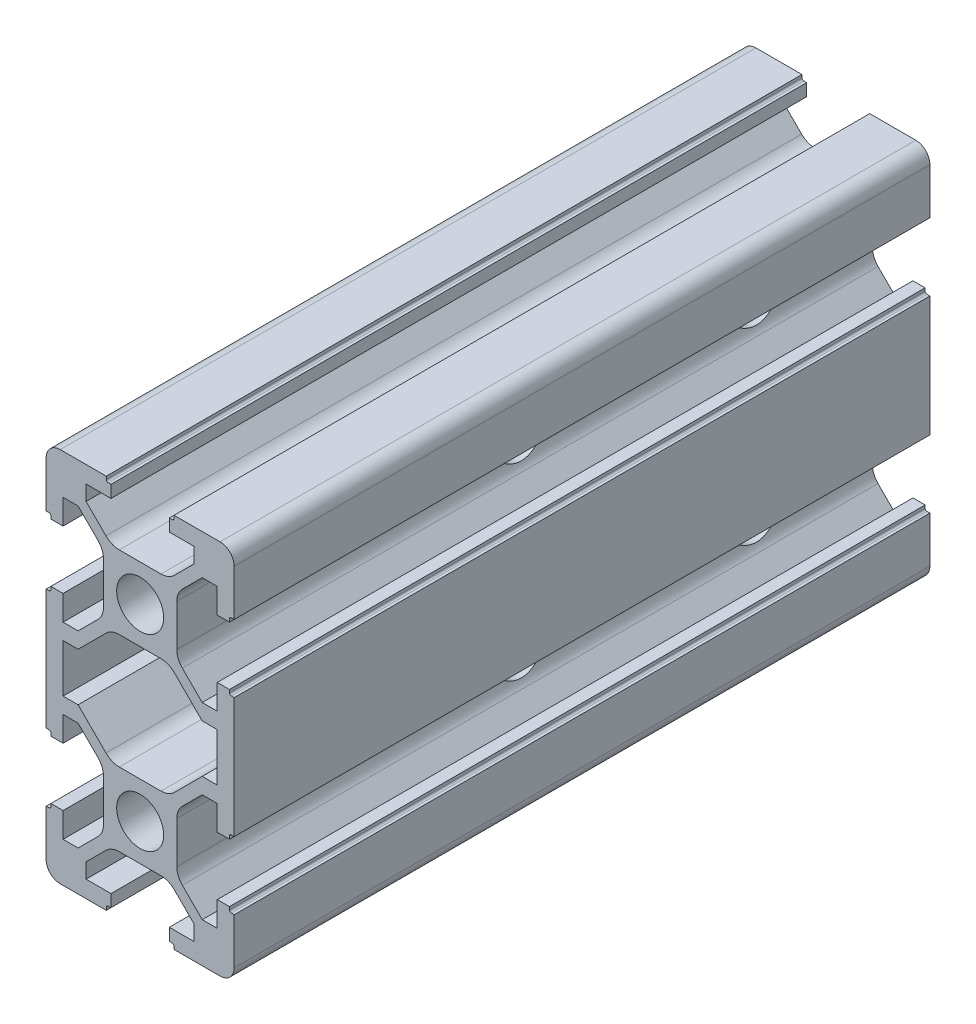
SolidWorks part; units mm, degrees
ref_plane "Alzado" through (0, 0, 0) normal (0, 0, 1) x (1, 0, 0)
ref_plane "Planta" through (0, 0, 0) normal (0, 1, 0) x (1, 0, 0)
ref_plane "Vista lateral" through (0, 0, 0) normal (1, 0, 0) x (0, 0, -1)
sketch "Croquis1" plane through (0, 0, 0) normal (0, 0, 1) x (1, 0, 0)
  line L0 (0, 0) -> (-10, -10) construction
  line L32 (0, 0) -> (-3.9, 0) construction
  line L58 (0, 0) -> (0, -3.9) construction
  line L60 (-4.4858, -3.6373) -> (-6.6, -5.7515)
  line L61 (-6.6, -5.7515) -> (-8.2, -5.7515)
  line L110 (-8.2, -5.7515) -> (-8.2, -3.1)
  line L111 (-8.2, -3.1) -> (-9.5, -3.1)
  line L112 (-9.5, -3.1) -> (-9.5, -3.4)
  line L113 (-9.7, -3.6) -> (-10, -3.6)
  line L114 (-10, -3.6) -> (-10, -8.5)
  line L115 (-3.6373, -4.4858) -> (-5.7515, -6.6)
  line L116 (-5.7515, -6.6) -> (-5.7515, -8.2)
  line L117 (-3.1, -8.2) -> (-3.1, -9.5)
  line L118 (-5.7515, -8.2) -> (-3.1, -8.2)
  line L119 (-3.1, -9.5) -> (-3.4, -9.5)
  line L120 (-3.6, -9.7) -> (-3.6, -10)
  line L121 (-3.6, -10) -> (-8.5, -10)
  line L122 (9.7, -3.6) -> (10, -3.6)
  line L123 (9.5, -3.1) -> (9.5, -3.4)
  line L124 (8.2, -3.1) -> (9.5, -3.1)
  line L125 (3.6, -10) -> (8.5, -10)
  line L126 (3.6, -9.7) -> (3.6, -10)
  line L127 (3.1, -9.5) -> (3.4, -9.5)
  line L128 (5.7515, -8.2) -> (3.1, -8.2)
  line L129 (3.1, -8.2) -> (3.1, -9.5)
  line L130 (5.7515, -6.6) -> (5.7515, -8.2)
  line L131 (3.6373, -4.4858) -> (5.7515, -6.6)
  line L132 (10, -3.6) -> (10, -8.5)
  line L133 (8.2, -5.7515) -> (8.2, -3.1)
  line L134 (6.6, -5.7515) -> (8.2, -5.7515)
  line L135 (4.4858, -3.6373) -> (6.6, -5.7515)
  line L136 (5.7515, 8.2) -> (3.1, 8.2)
  line L137 (3.6, 10) -> (8.5, 10)
  line L138 (-9.7, 3.6) -> (-10, 3.6)
  line L139 (-9.5, 3.1) -> (-9.5, 3.4)
  line L140 (-8.2, 3.1) -> (-9.5, 3.1)
  line L141 (-8.2, 5.7515) -> (-8.2, 3.1)
  line L142 (-6.6, 5.7515) -> (-8.2, 5.7515)
  line L143 (-4.4858, 3.6373) -> (-6.6, 5.7515)
  line L144 (3.1, 8.2) -> (3.1, 9.5)
  line L145 (3.1, 9.5) -> (3.4, 9.5)
  line L146 (3.6, 9.7) -> (3.6, 10)
  line L147 (-3.6, 10) -> (-8.5, 10)
  line L148 (-3.6, 9.7) -> (-3.6, 10)
  line L149 (-3.1, 9.5) -> (-3.4, 9.5)
  line L150 (-5.7515, 8.2) -> (-3.1, 8.2)
  line L151 (-3.1, 8.2) -> (-3.1, 9.5)
  line L152 (-5.7515, 6.6) -> (-5.7515, 8.2)
  line L153 (-3.6373, 4.4858) -> (-5.7515, 6.6)
  line L154 (-10, 3.6) -> (-10, 8.5)
  line L155 (4.4858, 3.6373) -> (6.6, 5.7515)
  line L156 (6.6, 5.7515) -> (8.2, 5.7515)
  line L157 (8.2, 5.7515) -> (8.2, 3.1)
  line L158 (10, 3.6) -> (10, 8.5)
  line L159 (3.6373, 4.4858) -> (5.7515, 6.6)
  line L160 (5.7515, 6.6) -> (5.7515, 8.2)
  line L161 (8.2, 3.1) -> (9.5, 3.1)
  line L162 (9.5, 3.1) -> (9.5, 3.4)
  line L163 (9.7, 3.6) -> (10, 3.6)
  line L164 (-3.9, 2.223) -> (-3.9, -2.223)
  line L165 (-2.223, -3.9) -> (2.223, -3.9)
  line L166 (3.9, -2.223) -> (3.9, 2.223)
  line L167 (2.223, 3.9) -> (-2.223, 3.9)
  circle A2 centre (0, 0) radius 2.5
  arc A3 (8.5, -10) -> (10, -8.5) centre (8.5, -8.5) ccw
  arc A4 (8.5, 10) -> (10, 8.5) centre (8.5, 8.5) cw
  arc A5 (-8.5, 10) -> (-10, 8.5) centre (-8.5, 8.5) ccw
  arc A6 (-10, -8.5) -> (-8.5, -10) centre (-8.5, -8.5) ccw
  arc A7 (-3.9, -2.223) -> (-4.4858, -3.6373) centre (-5.9, -2.223) cw
  arc A8 (4.4858, -3.6373) -> (3.9, -2.223) centre (5.9, -2.223) cw
  arc A9 (4.4858, 3.6373) -> (3.9, 2.223) centre (5.9, 2.223) ccw
  arc A10 (3.6373, 4.4858) -> (2.223, 3.9) centre (2.223, 5.9) cw
  arc A11 (-3.6373, 4.4858) -> (-2.223, 3.9) centre (-2.223, 5.9) ccw
  arc A12 (-4.4858, 3.6373) -> (-3.9, 2.223) centre (-5.9, 2.223) cw
  arc A13 (3.6373, -4.4858) -> (2.223, -3.9) centre (2.223, -5.9) ccw
  arc A14 (-3.6373, -4.4858) -> (-2.223, -3.9) centre (-2.223, -5.9) cw
  arc A15 (-3.4, -9.5) -> (-3.6, -9.7) centre (-3.4, -9.7) ccw
  arc A16 (3.6, -9.7) -> (3.4, -9.5) centre (3.4, -9.7) ccw
  arc A17 (9.7, -3.6) -> (9.5, -3.4) centre (9.7, -3.4) cw
  arc A18 (9.5, 3.4) -> (9.7, 3.6) centre (9.7, 3.4) cw
  arc A19 (3.4, 9.5) -> (3.6, 9.7) centre (3.4, 9.7) ccw
  arc A20 (-9.7, 3.6) -> (-9.5, 3.4) centre (-9.7, 3.4) cw
  arc A21 (-3.6, 9.7) -> (-3.4, 9.5) centre (-3.4, 9.7) ccw
  arc A22 (-9.5, -3.4) -> (-9.7, -3.6) centre (-9.7, -3.4) cw
  point P0 (0, 0)
  point P22 (10, -10)
  point P78 (10, 10)
  point P81 (-10, 10)
  point P90 (-3.9, -3.0515)
  point P93 (3.9, -3.0515)
  point P96 (3.9, 3.0515)
  point P99 (3.0515, 3.9)
  point P102 (-3.0515, 3.9)
  point P105 (-3.9, 3.0515)
  point P108 (3.0515, -3.9)
  point P111 (-3.0515, -3.9)
  point P116 (-3.6, -9.5)
  point P119 (3.6, -9.5)
  point P122 (9.5, -3.6)
  point P125 (9.5, 3.6)
  point P128 (3.6, 9.5)
  point P131 (-9.5, 3.6)
  point P134 (-3.6, 9.5)
  point P137 (-9.5, -3.6)
  dimension "D10" = 20
  dimension "D1" = 5
  dimension "D11" = 1.5
  dimension "D13" = 2
  dimension "D15" = 0.2
  dimension "D2" = 6.2
  dimension "D3" = 7.2
  dimension "D4" = 0.5
  dimension "D5" = 3.4
  dimension "D6" = 11.5029
  dimension "D7" = 6.1
  dimension "D8" = 1.8
  dimension "D9" = 1.2
extrude "Saliente-Extruir1" [suppressed] add sketch "Croquis1" along normal mid plane 100
sketch "Croquis3" plane through (0, 0, 0) normal (0, 0, 1) x (1, 0, 0)
  line L0 (-3.6363, -5.5152) -> (-6.6, -2.5556)
  line L3 (0, 0) -> (-10, 0) construction
  line L5 (-6.6, -2.5556) -> (-8.2, -2.5556)
  line L7 (0, -13.9) -> (0, -6.1) construction
  line L56 (-9.5, -13.1015) -> (-9.5, -13.4015)
  line L57 (-8.2, -13.1015) -> (-9.5, -13.1015)
  line L58 (-8.2, -15.7515) -> (-8.2, -13.1015)
  line L59 (-6.6, -15.7515) -> (-8.2, -15.7515)
  line L60 (-4.4858, -13.6373) -> (-6.6, -15.7515)
  line L61 (-3.9, -7.777) -> (-3.9, -12.223)
  line L62 (-6.6, -4.2515) -> (-4.4868, -6.3618)
  line L63 (-8.2, -4.2515) -> (-6.6, -4.2515)
  line L64 (-8.2, -6.9015) -> (-8.2, -4.2515)
  line L65 (-9.5, -6.9015) -> (-8.2, -6.9015)
  line L66 (-9.5, -6.6015) -> (-9.5, -6.9015)
  line L67 (-10, -6.4015) -> (-9.7, -6.4015)
  line L68 (-5.7515, -16.6) -> (-3.6373, -14.4858)
  line L69 (-5.7515, -18.2) -> (-5.7515, -16.6)
  line L70 (-3.1015, -18.2) -> (-5.7515, -18.2)
  line L71 (-3.1015, -19.5) -> (-3.1015, -18.2)
  line L72 (-3.4015, -19.5) -> (-3.1015, -19.5)
  line L73 (-3.6015, -20) -> (-3.6015, -19.7)
  line L74 (-8.5, -20) -> (-3.6015, -20)
  line L75 (-10, -13.6015) -> (-10, -18.5)
  line L76 (-9.7, -13.6015) -> (-10, -13.6015)
  line L102 (-10, -6.4015) -> (-10, 6.4015)
  line L103 (-8.2, -2.5556) -> (-8.2, 2.5556)
  line L104 (-2.223, -6.1) -> (2.223, -6.1)
  line L105 (-2.223, -13.9) -> (2.223, -13.9)
  line L106 (8.2, -2.5556) -> (8.2, 2.5556)
  line L107 (10, -6.4015) -> (10, 6.4015)
  line L108 (9.7, -13.6015) -> (10, -13.6015)
  line L109 (10, -13.6015) -> (10, -18.5)
  line L110 (8.5, -20) -> (3.6015, -20)
  line L111 (3.6015, -20) -> (3.6015, -19.7)
  line L112 (3.4015, -19.5) -> (3.1015, -19.5)
  line L113 (3.1015, -19.5) -> (3.1015, -18.2)
  line L114 (3.1015, -18.2) -> (5.7515, -18.2)
  line L115 (5.7515, -18.2) -> (5.7515, -16.6)
  line L116 (5.7515, -16.6) -> (3.6373, -14.4858)
  line L117 (10, -6.4015) -> (9.7, -6.4015)
  line L118 (9.5, -6.6015) -> (9.5, -6.9015)
  line L119 (9.5, -6.9015) -> (8.2, -6.9015)
  line L120 (8.2, -6.9015) -> (8.2, -4.2515)
  line L121 (8.2, -4.2515) -> (6.6, -4.2515)
  line L122 (6.6, -4.2515) -> (4.4868, -6.3618)
  line L123 (3.9, -7.777) -> (3.9, -12.223)
  line L124 (4.4858, -13.6373) -> (6.6, -15.7515)
  line L125 (6.6, -15.7515) -> (8.2, -15.7515)
  line L126 (8.2, -15.7515) -> (8.2, -13.1015)
  line L127 (8.2, -13.1015) -> (9.5, -13.1015)
  line L128 (9.5, -13.1015) -> (9.5, -13.4015)
  line L129 (6.6, -2.5556) -> (8.2, -2.5556)
  line L130 (3.6363, -5.5152) -> (6.6, -2.5556)
  line L131 (3.6363, 5.5152) -> (6.6, 2.5556)
  line L132 (6.6, 2.5556) -> (8.2, 2.5556)
  line L133 (9.5, 13.1015) -> (9.5, 13.4015)
  line L134 (8.2, 13.1015) -> (9.5, 13.1015)
  line L135 (8.2, 15.7515) -> (8.2, 13.1015)
  line L136 (6.6, 15.7515) -> (8.2, 15.7515)
  line L137 (4.4858, 13.6373) -> (6.6, 15.7515)
  line L138 (3.9, 7.777) -> (3.9, 12.223)
  line L139 (6.6, 4.2515) -> (4.4868, 6.3618)
  line L140 (8.2, 4.2515) -> (6.6, 4.2515)
  line L141 (8.2, 6.9015) -> (8.2, 4.2515)
  line L142 (9.5, 6.9015) -> (8.2, 6.9015)
  line L143 (9.5, 6.6015) -> (9.5, 6.9015)
  line L144 (10, 6.4015) -> (9.7, 6.4015)
  line L145 (5.7515, 16.6) -> (3.6373, 14.4858)
  line L146 (5.7515, 18.2) -> (5.7515, 16.6)
  line L147 (3.1015, 18.2) -> (5.7515, 18.2)
  line L148 (3.1015, 19.5) -> (3.1015, 18.2)
  line L149 (3.4015, 19.5) -> (3.1015, 19.5)
  line L150 (3.6015, 20) -> (3.6015, 19.7)
  line L151 (8.5, 20) -> (3.6015, 20)
  line L152 (10, 13.6015) -> (10, 18.5)
  line L153 (9.7, 13.6015) -> (10, 13.6015)
  line L154 (-2.223, 13.9) -> (2.223, 13.9)
  line L155 (-2.223, 6.1) -> (2.223, 6.1)
  line L156 (-9.7, 13.6015) -> (-10, 13.6015)
  line L157 (-10, 13.6015) -> (-10, 18.5)
  line L158 (-8.5, 20) -> (-3.6015, 20)
  line L159 (-3.6015, 20) -> (-3.6015, 19.7)
  line L160 (-3.4015, 19.5) -> (-3.1015, 19.5)
  line L161 (-3.1015, 19.5) -> (-3.1015, 18.2)
  line L162 (-3.1015, 18.2) -> (-5.7515, 18.2)
  line L163 (-5.7515, 18.2) -> (-5.7515, 16.6)
  line L164 (-5.7515, 16.6) -> (-3.6373, 14.4858)
  line L165 (-10, 6.4015) -> (-9.7, 6.4015)
  line L166 (-9.5, 6.6015) -> (-9.5, 6.9015)
  line L167 (-9.5, 6.9015) -> (-8.2, 6.9015)
  line L168 (-8.2, 6.9015) -> (-8.2, 4.2515)
  line L169 (-8.2, 4.2515) -> (-6.6, 4.2515)
  line L170 (-6.6, 4.2515) -> (-4.4868, 6.3618)
  line L171 (-3.9, 7.777) -> (-3.9, 12.223)
  line L172 (-4.4858, 13.6373) -> (-6.6, 15.7515)
  line L173 (-6.6, 15.7515) -> (-8.2, 15.7515)
  line L174 (-8.2, 15.7515) -> (-8.2, 13.1015)
  line L175 (-8.2, 13.1015) -> (-9.5, 13.1015)
  line L176 (-9.5, 13.1015) -> (-9.5, 13.4015)
  line L177 (-6.6, 2.5556) -> (-8.2, 2.5556)
  line L178 (-3.6363, 5.5152) -> (-6.6, 2.5556)
  line L179 (0, -10) -> (-9.5607, -19.5607) construction
  circle A8 centre (0, -10) radius 2.5
  arc A20 (-4.4858, -13.6373) -> (-3.9, -12.223) centre (-5.9, -12.223) ccw
  arc A21 (-3.9, -7.777) -> (-4.4868, -6.3618) centre (-5.9, -7.777) ccw
  arc A22 (-9.5, -6.6015) -> (-9.7, -6.4015) centre (-9.7, -6.6015) ccw
  arc A23 (-3.6363, -5.5152) -> (-2.223, -6.1) centre (-2.223, -4.1) ccw
  arc A24 (-2.223, -13.9) -> (-3.6373, -14.4858) centre (-2.223, -15.9) ccw
  arc A25 (-3.4015, -19.5) -> (-3.6015, -19.7) centre (-3.4015, -19.7) ccw
  arc A26 (-10, -18.5) -> (-8.5, -20) centre (-8.5, -18.5) ccw
  arc A27 (-9.7, -13.6015) -> (-9.5, -13.4015) centre (-9.7, -13.4015) ccw
  arc A34 (9.7, -13.6015) -> (9.5, -13.4015) centre (9.7, -13.4015) cw
  arc A35 (10, -18.5) -> (8.5, -20) centre (8.5, -18.5) cw
  arc A36 (3.4015, -19.5) -> (3.6015, -19.7) centre (3.4015, -19.7) cw
  arc A37 (2.223, -13.9) -> (3.6373, -14.4858) centre (2.223, -15.9) cw
  arc A38 (3.6363, -5.5152) -> (2.223, -6.1) centre (2.223, -4.1) cw
  arc A39 (9.5, -6.6015) -> (9.7, -6.4015) centre (9.7, -6.6015) cw
  arc A40 (3.9, -7.777) -> (4.4868, -6.3618) centre (5.9, -7.777) cw
  arc A41 (4.4858, -13.6373) -> (3.9, -12.223) centre (5.9, -12.223) cw
  arc A42 (4.4858, 13.6373) -> (3.9, 12.223) centre (5.9, 12.223) ccw
  arc A43 (3.9, 7.777) -> (4.4868, 6.3618) centre (5.9, 7.777) ccw
  arc A44 (9.5, 6.6015) -> (9.7, 6.4015) centre (9.7, 6.6015) ccw
  arc A45 (3.6363, 5.5152) -> (2.223, 6.1) centre (2.223, 4.1) ccw
  arc A46 (2.223, 13.9) -> (3.6373, 14.4858) centre (2.223, 15.9) ccw
  arc A47 (3.4015, 19.5) -> (3.6015, 19.7) centre (3.4015, 19.7) ccw
  arc A48 (10, 18.5) -> (8.5, 20) centre (8.5, 18.5) ccw
  arc A49 (9.7, 13.6015) -> (9.5, 13.4015) centre (9.7, 13.4015) ccw
  arc A50 (-9.7, 13.6015) -> (-9.5, 13.4015) centre (-9.7, 13.4015) cw
  arc A51 (-10, 18.5) -> (-8.5, 20) centre (-8.5, 18.5) cw
  arc A52 (-3.4015, 19.5) -> (-3.6015, 19.7) centre (-3.4015, 19.7) cw
  arc A53 (-2.223, 13.9) -> (-3.6373, 14.4858) centre (-2.223, 15.9) cw
  arc A54 (-3.6363, 5.5152) -> (-2.223, 6.1) centre (-2.223, 4.1) cw
  arc A55 (-9.5, 6.6015) -> (-9.7, 6.4015) centre (-9.7, 6.6015) cw
  arc A56 (-3.9, 7.777) -> (-4.4868, 6.3618) centre (-5.9, 7.777) cw
  arc A57 (-4.4858, 13.6373) -> (-3.9, 12.223) centre (-5.9, 12.223) cw
  circle A58 centre (0, 10) radius 2.5
  point P59 (8.2, 0)
  point P63 (8.2, 0)
  point P159 (10, 0)
  point P160 (-8.2, 0)
  point P174 (-8.2, 0)
  point P190 (-3.9, -10)
  point P193 (0, -10)
  dimension "D8" = 2
  dimension "D9" = 1.5
  dimension "D11" = 5
  dimension "D13" = 0.2
  dimension "D1" = 40
  dimension "D2" = 11.5
  dimension "D3" = 6.2
  dimension "D4" = 1.8
  dimension "D5" = 0.5
  dimension "D6" = 3.4
  dimension "D7" = 20
  dimension "D10" = 1.2
  dimension "D12" = 7.8
  dimension "D14" = 20
extrude "Saliente-Extruir3" add sketch "Croquis3" along normal mid plane 350 separate body
sketch "Sketch1" plane through (0, 20, 0) normal (0, 1, 0) x (1, 0, 0)
  line L0 (10, 175) -> (8.5, 175) construction
  line L1 (8.5, -175) -> (10, -175) construction
  line L2 (10, -175) -> (10, 175) construction
  line L3 (8.5, 175) -> (3.6015, 175) construction
  line L4 (3.6015, 175) -> (3.6015, -175) construction
  line L5 (3.6015, -175) -> (8.5, -175) construction
  line L6 (3.6373, 175) -> (2.223, 175) construction
  line L7 (2.223, -175) -> (3.6373, -175) construction
  line L8 (3.6373, -175) -> (3.6373, 175) construction
  line L10 (-2.223, -175) -> (2.223, -175) construction
  line L11 (-2.223, 175) -> (-3.6373, 175) construction
  line L12 (-3.6373, 175) -> (-3.6373, -175) construction
  line L13 (-3.6373, -175) -> (-2.223, -175) construction
  line L14 (-3.6015, 175) -> (-8.5, 175) construction
  line L15 (-8.5, -175) -> (-3.6015, -175) construction
  line L16 (-3.6015, -175) -> (-3.6015, 175) construction
  line L17 (-8.5, 175) -> (-10, 175) construction
  line L18 (-10, 175) -> (-10, -175) construction
  line L19 (-10, -175) -> (-8.5, -175) construction
  line L20 (10, 175) -> (8.5, 175)
  line L21 (8.5, -175) -> (10, -175)
  line L22 (10, -175) -> (10, 101)
  line L23 (3.6373, 175) -> (3.6015, 175)
  line L24 (3.6015, 101) -> (3.6015, -175)
  line L25 (3.6015, -175) -> (8.5, -175)
  line L26 (3.6373, 175) -> (2.223, 175)
  line L27 (2.223, -175) -> (3.6373, -175)
  line L28 (3.6373, -175) -> (3.6373, 101)
  line L30 (-2.223, -175) -> (2.223, -175)
  line L31 (-3.6015, 175) -> (-3.6373, 175)
  line L32 (-3.6373, 101) -> (-3.6373, -175)
  line L33 (-3.6373, -175) -> (-2.223, -175)
  line L34 (-3.6015, 175) -> (-3.6373, 175)
  line L35 (-8.5, -175) -> (-3.6015, -175)
  line L36 (-3.6015, -175) -> (-3.6015, 101)
  line L37 (-8.5, 175) -> (-10, 175)
  line L38 (-10, 101) -> (-10, -175)
  line L39 (-10, -175) -> (-8.5, -175)
  line L40 (-10, 101) -> (10, 101)
  line L41 (10, 101) -> (10, -175)
  line L42 (10, -175) -> (8.5, -175)
  line L43 (10, -175) -> (-10, -175)
  line L44 (-10, -175) -> (-10, 101)
  line M6 (-8.5, 175) -> (-8.5, -175)
  line M7 (-8.5, -175) -> (-3.6015, -175)
  line M8 (-3.6015, -175) -> (-3.6015, 175)
  dimension "D1" = 350
  dimension "D2" = 276
extrude "Cut-Extrude3" cut sketch "Sketch1" against normal blind 100 contours L40 L28 L25 L21 L22 | L40 L33 L30 L27 L24 M8 | L40 L32 M6 M7 | L40 L38 L39 M6 | L40 L32 M7 M8 | L40 L24 L25 L28
sketch "Sketch2" plane through (10, 0, 0) normal (1, 0, 0) x (0, 0, -1)
  line L8 (101, 6.4015) -> (101, -6.4015) construction
  line L9 (101, -6.4015) -> (175, -6.4015) construction
  line L10 (175, -6.4015) -> (175, 6.4015) construction
  line L11 (175, 6.4015) -> (101, 6.4015) construction
  line L12 (101, 20) -> (101, 18.5)
  line L14 (175, 18.5) -> (175, 20)
  line L16 (101, -18.5) -> (101, -20)
  line L18 (175, -20) -> (175, -18.5)
  line L20 (101, 6.4015) -> (101, -6.4015)
  line L21 (101, -6.4015) -> (175, -6.4015)
  line L22 (175, -6.4015) -> (175, 6.4015)
  line L23 (175, 6.4015) -> (101, 6.4015)
  line L24 (101, 18.5) -> (101, -18.2)
  line L25 (175, 18.5) -> (175, -18.5)
  line L26 (125, 20) -> (125, -20)
  line L27 (125, 0) -> (175, 0) construction
  line L28 (125, -20) -> (175, -20)
  line L29 (150, 20) -> (150, -20) construction
  line L30 (101, 18.5) -> (175, 18.5) construction
  line L31 (101, 20) -> (175, 20) construction
  line L32 (101, 18.5) -> (175, 18.5)
  line L33 (101, 20) -> (175, 20)
  line L34 (101, -20) -> (175, -20) construction
  line L35 (101, -18.5) -> (175, -18.5) construction
  line L36 (101, -20) -> (175, -20)
  line L37 (101, -18.5) -> (175, -18.5)
  circle A0 centre (137.5, 10) radius 3
  circle A1 centre (162.5, 10) radius 3
  circle A2 centre (162.5, -10) radius 3
  circle A3 centre (137.5, -10) radius 3
  point P21 (137.5, 10)
  point P23 (162.5, 10)
  point P25 (162.5, -10)
  point P27 (137.5, -10)
  dimension "D3" = 6
  dimension "D1" = 50
  dimension "D2" = 25
  dimension "D5" = 12.5
  dimension "D6" = 74
hole_wizard "Ø6.0mm Dowel Hole1" positions "Sketch2" profile "Sketch4" hole size "Ø6.0" standard "ANSI Metric" end condition through all
sketch "Sketch4" plane through (10, -10, -137.5) normal (0, 1, 0) x (0, 0, -1)
  line L0 (0, 0) -> (0, 20)
  line L1 (0, 20) -> (3, 20)
  line L2 (3, 20) -> (3, 0)
  line L5 (3, 0) -> (0, 0)
  line L11 (0, -6.35) -> (0, 107.95) construction
  dimension "Thru Hole Dia." = 6
  dimension "Thru Hole Depth" = 20
